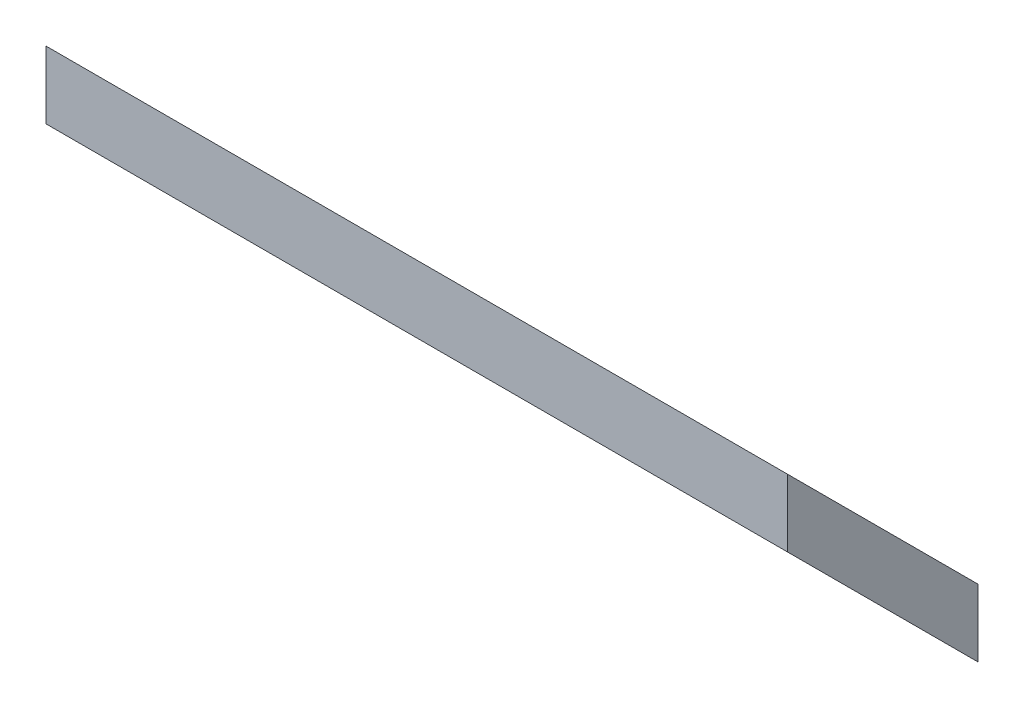
SolidWorks part; units mm, degrees
ref_plane "Front Plane" through (0, 0, 0) normal (0, 0, 1) x (1, 0, 0)
ref_plane "Top Plane" through (0, 0, 0) normal (0, 1, 0) x (1, 0, 0)
ref_plane "Right Plane" through (0, 0, 0) normal (1, 0, 0) x (0, 0, -1)
sketch "Sketch1" plane through (0, 0, 0) normal (0, 0, 1) x (1, 0, 0)
  line L0 (-69.85, 0) -> (69.85, 0)
  line L4 (69.85, 12.7) -> (-69.85, 12.7)
  line L5 (0, 12.7) -> (0, 0) construction
  line L6 (69.85, 0) -> (103.6536, 0) construction
  line L10 (69.85, 12.7) -> (69.85, 0)
  line L11 (-69.85, 12.7) -> (-69.85, 0)
  dimension "D1" = 69.85
  dimension "D2" = 69.85
  dimension "D3" = 12.7
  dimension "D6" = 12.7
sketch "Sketch2" plane through (0, 0, 0) normal (1, 0, 0) x (0, 0, -1)
  line L0 (0, 0) -> (-35.921, 35.921)
  line L1 (0, 0) -> (-49.4445, 0) construction
  dimension "D1" = 45
  dimension "D2" = 50.8
sweep "Sweep1" add profiles "Sketch1" path "Sketch2"
